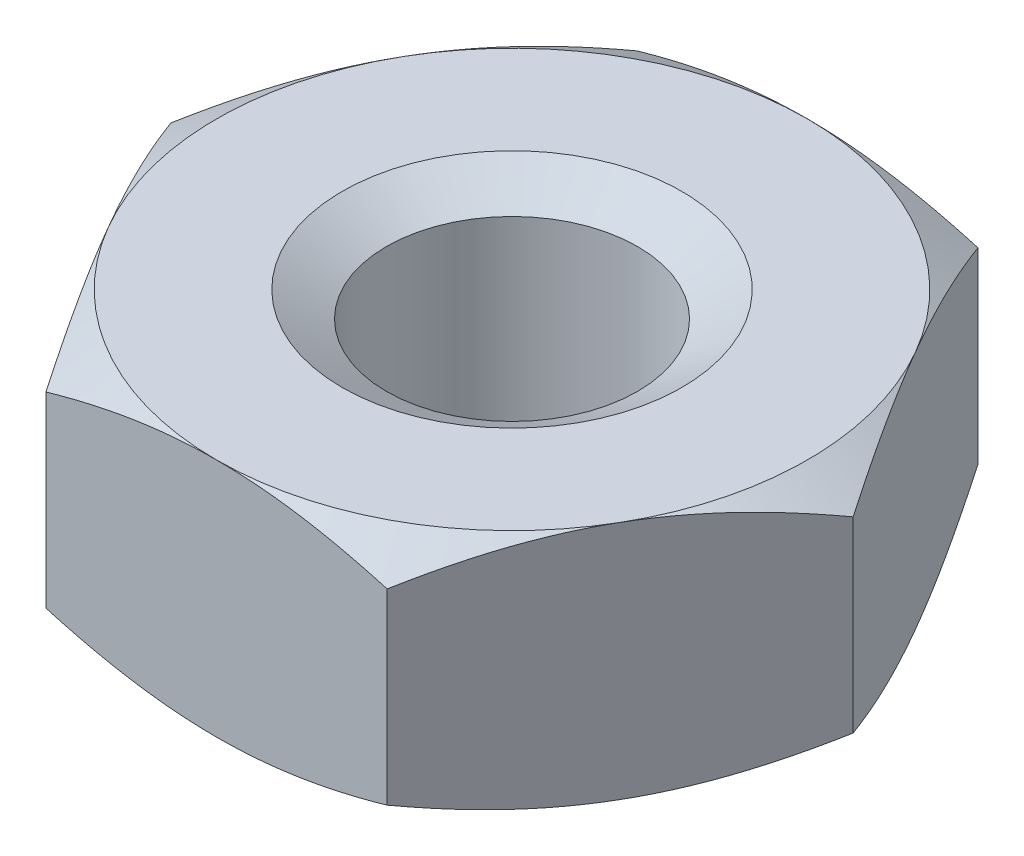
SolidWorks part; units mm, degrees
ref_plane "Přední rovina" through (0, 0, 0) normal (0, 0, 1) x (1, 0, 0)
ref_plane "Vrchní rovina" through (0, 0, 0) normal (0, 1, 0) x (1, 0, 0)
ref_plane "Pravá rovina" through (0, 0, 0) normal (1, 0, 0) x (0, 0, -1)
sketch "Skica1" plane through (0, 0, 0) normal (0, 1, 0) x (1, 0, 0)
  line L1 (1.8475, 0) -> (0.9238, 1.6)
  line L2 (0.9238, 1.6) -> (-0.9238, 1.6)
  line L3 (-0.9238, 1.6) -> (-1.8475, 0)
  line L4 (-1.8475, 0) -> (-0.9238, -1.6)
  line L5 (-0.9238, -1.6) -> (0.9238, -1.6)
  line L6 (0.9238, -1.6) -> (1.8475, 0)
  circle A0 centre (0, 0) radius 1.6 construction
  dimension "s" = 3.2
extrude "Vysunout1" add sketch "Skica1" along normal mid plane 1.3
sketch "Skica2" plane through (0, 0, 0) normal (1, 0, 0) x (0, 0, -1)
  line L0 (1.6, 0.65) -> (2.7258, 0.65)
  line L1 (2.7258, 0.65) -> (2.7258, -0.65)
  line L2 (2.7258, -0.65) -> (1.6, -0.65)
  line L3 (1.6, -0.65) -> (2.7258, 0)
  line L4 (2.7258, 0) -> (1.6, 0.65)
  line L5 (0, 0.65) -> (0, 0) construction
  dimension "D1" = 30
revolve "Odebrat otočením1" cut sketch "Skica2" angle 360 about L5
sketch "Skica3" plane through (0, 0.65, 0) normal (0, 1, 0) x (-1, 0, 0)
  circle A0 centre (0, 0) radius 0.68
  dimension "M´" = 1.36
extrude "Odebrat vysunutím1" cut sketch "Skica3" against normal through all
cosmetic thread "Kosmetický závit1" parameters "M"=1.6
sketch "Skica4" plane through (0, 0.65, 0) normal (0, 1, 0) x (-1, 0, 0)
  circle A0 centre (0, 0) radius 0.92
  dimension "da" = 1.84
extrude "Odebrat vysunutím2" cut sketch "Skica4" against normal blind 1.3 draft 60
mirror "Zrcadlit1" about plane through (0, 0, 0) normal (0, 1, 0) of "Odebrat vysunutím2"
